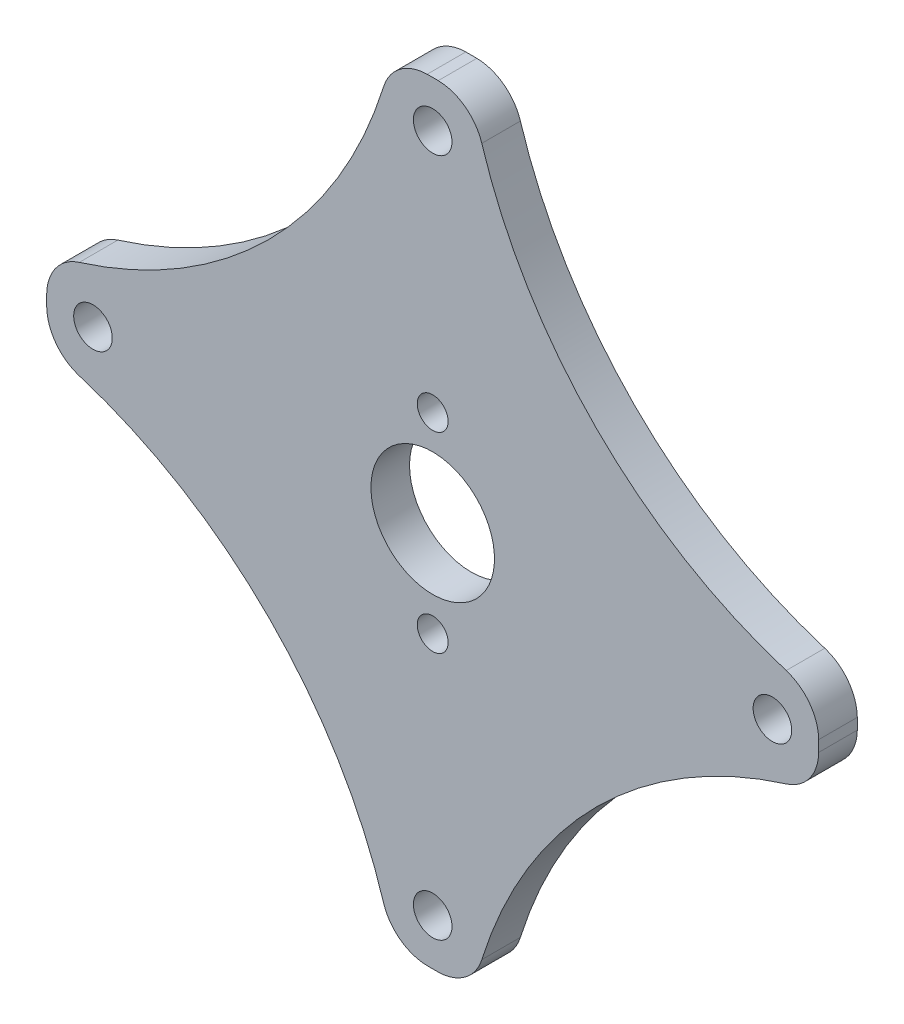
SolidWorks part; units mm, degrees
ref_plane "前视基准面" through (0, 0, 0) normal (0, 0, 1) x (1, 0, 0)
ref_plane "上视基准面" through (0, 0, 0) normal (0, 1, 0) x (1, 0, 0)
ref_plane "右视基准面" through (0, 0, 0) normal (1, 0, 0) x (0, 0, -1)
other "Configuration Table"
sketch "草图1" plane through (0, 0, 0) normal (0, 0, 1) x (1, 0, 0)
  line L0 (0, 0) -> (0, 22) construction
  line L1 (0, 0) -> (22, 0) construction
  circle A0 centre (0, 0) radius 22 construction
  circle A1 centre (0, 0) radius 16.5 construction
  circle A2 centre (0, 0) radius 25
  circle A3 centre (0, 22) radius 1.25
  circle A4 centre (22, 0) radius 1.25
  circle A5 centre (0, -22) radius 1.25
  circle A6 centre (-22, 0) radius 1.25
  dimension "D1" = 44
  dimension "D2" = 33
  dimension "D3" = 3
  dimension "D4" = 2.5
  dimension "D6" = 90
  dimension "D5" = 3
extrude "凸台-拉伸1" add sketch "草图1" along normal blind 2.5
sketch "草图3" plane through (0, 0, 0) normal (0, 0, -1) x (-1, 0, 0)
  line L0 (0, 0) -> (0, 22) construction
  circle A0 centre (0, 0) radius 10.5
  circle A1 centre (0, 0) radius 4
  circle A2 centre (0, 6.2) radius 1
  circle A3 centre (0, -6.2) radius 1
  dimension "D1" = 21
  dimension "D2" = 8
  dimension "D3" = 2
  dimension "D4" = 2
  dimension "D5" = 6.2
  dimension "D6" = 6.2
extrude "切除-拉伸2" cut sketch "草图3" against normal through all both and the other way through all contours A2 | A1 | A3
sketch "草图5" plane through (0, 0, 0) normal (0, 0, -1) x (-1, 0, 0)
  line L0 (-31.8198, 31.8198) -> (0, 0) construction
  line L1 (-22, 0) -> (0, 0) construction
  arc A0 (-24.8604, 2.6382) -> (-2.6382, 24.8604) centre (-31.8198, 31.8198) ccw
  circle A5 centre (0, 0) radius 25 construction
  arc A6 (2.6382, 24.8604) -> (24.8604, 2.6382) centre (31.8198, 31.8198) ccw
  circle A7 centre (0, 0) radius 25
  circle A8 centre (0, 0) radius 25
  arc A9 (24.8604, -2.6382) -> (2.6382, -24.8604) centre (31.8198, -31.8198) ccw
  arc A10 (-2.6382, -24.8604) -> (-24.8604, -2.6382) centre (-31.8198, -31.8198) ccw
  point P22 (0, 0)
  circle M3 centre (0, 0) radius 25
  dimension "D2" = 30
  dimension "D1" = 0
  dimension "D4" = 45
  dimension "D5" = 4
  dimension "D3" = 45
extrude "切除-拉伸5" cut sketch "草图5" against normal blind 10 contours A0 M3 | A8 A10 | A8 A9 | A6 M3
fillet "圆角2" radius 3 8 edges at (24.8604, 2.6382, 1.25) (2.6382, 24.8604, 1.25) (-2.6382, 24.8604, 1.25) (-24.8604, 2.6382, 1.25) (-24.8604, -2.6382, 1.25) (-2.6382, -24.8604, 1.25) (2.6382, -24.8604, 1.25) (24.8604, -2.6382, 1.25)
